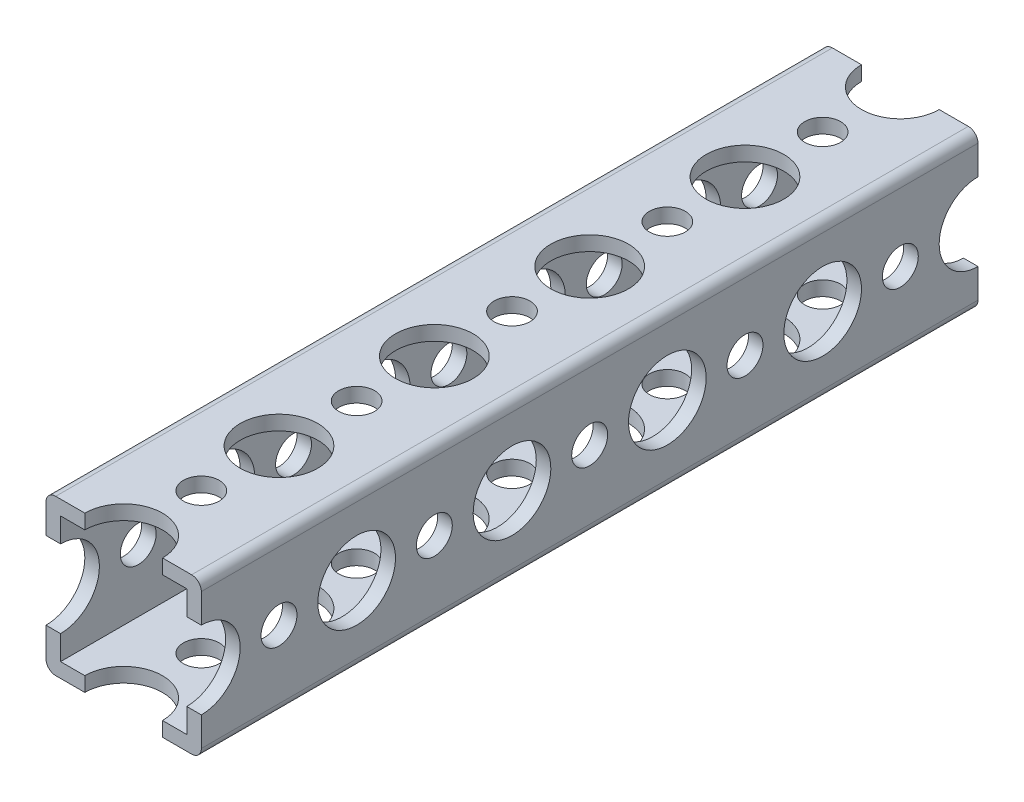
SolidWorks part; units mm, degrees
ref_plane "Front Plane" through (0, 0, 0) normal (0, 0, 1) x (1, 0, 0)
ref_plane "Top Plane" through (0, 0, 0) normal (0, 1, 0) x (1, 0, 0)
ref_plane "Right Plane" through (0, 0, 0) normal (1, 0, 0) x (0, 0, -1)
sketch "Sketch1" plane through (0, 0, 0) normal (0, 0, 1) x (1, 0, 0)
  line L1 (0, 0) -> (16, 0)
  line L2 (0, 0) -> (0, 16)
  line L3 (0, 16) -> (16, 16)
  line L4 (16, 0) -> (16, 16)
  dimension "D1" = 16
  dimension "D2" = 16
extrude "Extrude1" add sketch "Sketch1" against normal blind 80
sketch "Sketch2" plane through (0, 0, 0) normal (0, 0, 1) x (1, 0, 0)
  line L0 (-1.7793, 8) -> (18.8812, 8) construction
  line L1 (8, 16.9255) -> (8, -0.6999) construction
  line L3 (1.5, 14.5) -> (14.5, 14.5)
  line L4 (1.5, 14.5) -> (1.5, 1.5)
  line L5 (1.5, 1.5) -> (14.5, 1.5)
  line L6 (14.5, 14.5) -> (14.5, 1.5)
  line L7 (1.5, 14.5) -> (14.5, 1.5) construction
  line L8 (1.5, 1.5) -> (14.5, 14.5) construction
  point P4 (8, 8)
  dimension "D1" = 13
  dimension "D2" = 13
extrude "Extrude2" cut sketch "Sketch2" against normal through all
sketch "Sketch3" plane through (0, 16, 0) normal (0, 1, 0) x (1, 0, 0)
  line L0 (-10.6019, 48) -> (25.4979, 48) construction
  line L1 (8, -3.3001) -> (8, 305.034) construction
  line L2 (-10.6019, 80) -> (44.8988, 80) construction
  line L4 (16, 0) -> (0, 0) construction
  line L5 (-19.3069, 144) -> (85.0309, 144) construction
  circle A0 centre (8, 64) radius 4
  circle A1 centre (8, 32) radius 4
  circle A3 centre (8, 0) radius 4
  circle A4 centre (8, 96) radius 4
  circle A5 centre (8, 128) radius 4
  circle A6 centre (8, 160) radius 4
  circle A7 centre (8, 192) radius 4
  circle A8 centre (8, 224) radius 4
  circle A9 centre (8, 256) radius 4
  circle B0 centre (8, 48) radius 4
  circle B1 centre (8, 56) radius 1.85
  circle B2 centre (8, 40) radius 1.85
  circle B3 centre (8, 80) radius 4
  circle B4 centre (8, 88) radius 1.85
  circle B5 centre (8, 72) radius 1.85
  circle B6 centre (8, 16) radius 4
  circle B7 centre (8, 24) radius 1.85
  circle B8 centre (8, 8) radius 1.85
  circle B9 centre (8, 112) radius 4
  circle B10 centre (8, 120) radius 1.85
  circle B11 centre (8, 104) radius 1.85
  circle B12 centre (8, 144) radius 4
  circle B13 centre (8, 152) radius 1.85
  circle B14 centre (8, 136) radius 1.85
  circle B15 centre (8, 176) radius 4
  circle B16 centre (8, 184) radius 1.85
  circle B17 centre (8, 168) radius 1.85
  circle B18 centre (8, 208) radius 4
  circle B19 centre (8, 216) radius 1.85
  circle B20 centre (8, 200) radius 1.85
  circle B21 centre (8, 240) radius 4
  circle B22 centre (8, 248) radius 1.85
  circle B23 centre (8, 232) radius 1.85
  dimension "D1" = 24
  dimension "D2" = 16
  dimension "D4" = 16
  dimension "D5" = 32
  dimension "D7" = 16
  dimension "D13" = 48
  dimension "D3" = 24
  dimension "D6" = 64
  dimension "D8" = 48
  dimension "D9" = 32
  dimension "D10" = 64
  dimension "D11" = 96
  dimension "D14" = 16
  dimension "D15" = 80
  dimension "D16" = 112
sketch_block_instance "Block2-1"
sketch_block "Block2"
sketch_block_instance "Block2-4"
sketch_block_instance "Block2-6"
sketch_block_instance "Block2-11"
sketch_block_instance "Block2-12"
sketch_block_instance "Block2-17"
sketch_block_instance "Block2-18"
sketch_block_instance "Block2-19"
extrude "Extrude3" cut sketch "Sketch3" against normal through all
sketch "Sketch4" plane through (16, 0, 0) normal (1, 0, 0) x (0, 0, -1)
  line L0 (-4.9809, 8) -> (308.0277, 8) construction
  line L1 (48, 20.3919) -> (48, -4.2435) construction
  line L2 (0, 0) -> (0, 16) construction
  line L4 (80, -7.5844) -> (80, 23.8371) construction
  line L5 (144, 22.3836) -> (144, -28.3788) construction
  circle A0 centre (32, 8) radius 4
  circle A1 centre (64, 8) radius 4
  circle A2 centre (0, 8) radius 4
  circle A4 centre (96, 8) radius 4
  circle A5 centre (128, 8) radius 4
  circle A6 centre (160, 8) radius 4
  circle A7 centre (192, 8) radius 4
  circle A8 centre (224, 8) radius 4
  circle A9 centre (256, 8) radius 4
  circle B0 centre (48, 8.0742) radius 4
  circle B1 centre (40, 8.0742) radius 1.85
  circle B2 centre (56, 8.0742) radius 1.85
  circle B3 centre (80, 8) radius 4
  circle B4 centre (72, 8) radius 1.85
  circle B5 centre (88, 8) radius 1.85
  circle B6 centre (16, 8) radius 4
  circle B7 centre (8, 8) radius 1.85
  circle B8 centre (24, 8) radius 1.85
  circle B9 centre (112, 8) radius 4
  circle B10 centre (104, 8) radius 1.85
  circle B11 centre (120, 8) radius 1.85
  circle B12 centre (144, 8) radius 4
  circle B13 centre (136, 8) radius 1.85
  circle B14 centre (152, 8) radius 1.85
  circle B15 centre (176, 8) radius 4
  circle B16 centre (168, 8) radius 1.85
  circle B17 centre (184, 8) radius 1.85
  circle B18 centre (208, 8) radius 4
  circle B19 centre (200, 8) radius 1.85
  circle B20 centre (216, 8) radius 1.85
  circle B21 centre (240, 8) radius 4
  circle B22 centre (232, 8) radius 1.85
  circle B23 centre (248, 8) radius 1.85
  dimension "D3" = 16
  dimension "D5" = 32
  dimension "D7" = 16
  dimension "D13" = 16
  dimension "D1" = 24
  dimension "D2" = 24
  dimension "D4" = 16
  dimension "D6" = 64
  dimension "D8" = 48
  dimension "D9" = 32
  dimension "D10" = 64
  dimension "D11" = 96
  dimension "D14" = 48
  dimension "D15" = 80
  dimension "D16" = 112
sketch_block_instance "Block2-8"
sketch_block_instance "Block2-9"
sketch_block_instance "Block2-10"
sketch_block_instance "Block2-14"
sketch_block_instance "Block2-15"
sketch_block_instance "Block2-22"
sketch_block_instance "Block2-23"
sketch_block_instance "Block2-24"
extrude "Extrude4" cut sketch "Sketch4" against normal through all
fillet "Fillet1" radius 1 4 edges at (0, 0, -40) (16, 0, -40) (0, 16, -40) (16, 16, -40)
